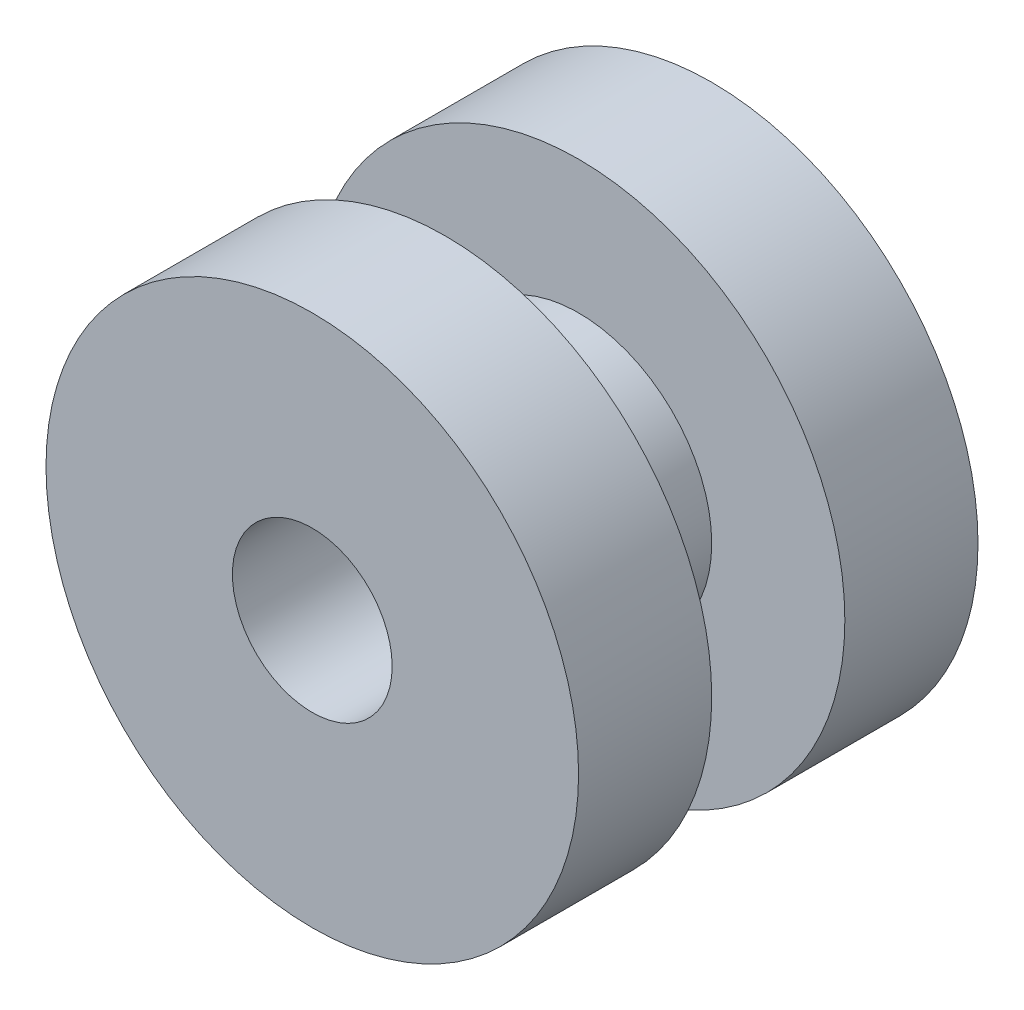
SolidWorks part; units mm, degrees
ref_plane "Front Plane" through (0, 0, 0) normal (0, 0, 1) x (1, 0, 0)
ref_plane "Top Plane" through (0, 0, 0) normal (0, 1, 0) x (1, 0, 0)
ref_plane "Right Plane" through (0, 0, 0) normal (1, 0, 0) x (0, 0, -1)
sketch "Sketch1" plane through (0, 0, 0) normal (0, 0, 1) x (1, 0, 0)
  circle A0 centre (0, 0) radius 10
  point P3 (0, 0)
extrude "Boss-Extrude7" add sketch "Sketch1" along normal blind 5
sketch "Sketch8" plane through (0, 0, 5) normal (0, 0, 1) x (1, 0, 0)
  circle A0 centre (0, 0) radius 5
extrude "Boss-Extrude8" add sketch "Sketch8" along normal blind 5
sketch "Sketch9" plane through (0, 0, 10) normal (0, 0, 1) x (1, 0, 0)
  circle A0 centre (0, 0) radius 10
extrude "Boss-Extrude9" add sketch "Sketch9" along normal blind 5
sketch "Sketch10" plane through (0, 0, 15) normal (0, 0, 1) x (1, 0, 0)
  circle A0 centre (0, 0) radius 3
extrude "Cut-Extrude4" cut sketch "Sketch10" against normal through all
